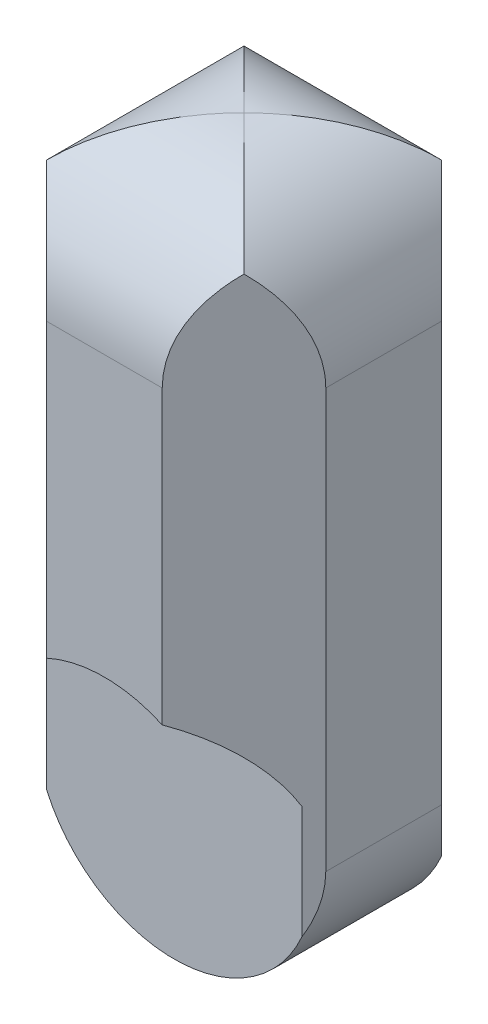
SolidWorks part; units mm, degrees
ref_plane "Front" through (0, 0, 0) normal (0, 0, 1) x (1, 0, 0)
ref_plane "Top" through (0, 0, 0) normal (0, 1, 0) x (1, 0, 0)
ref_plane "Right" through (0, 0, 0) normal (1, 0, 0) x (0, 0, -1)
sketch "草图2" plane through (0, 0, 0) normal (0, 1, 0) x (1, 0, 0)
  line L1 (8, 3.3137) -> (3.3137, 8)
  line L2 (3.3137, 8) -> (-3.3137, 8)
  line L3 (-3.3137, 8) -> (-8, 3.3137)
  line L4 (-8, 3.3137) -> (-8, -3.3137)
  line L5 (-8, -3.3137) -> (-3.3137, -8)
  line L6 (-3.3137, -8) -> (3.3137, -8)
  line L7 (3.3137, -8) -> (8, -3.3137)
  line L8 (8, -3.3137) -> (8, 3.3137)
  circle A0 centre (0, 0) radius 8 construction
extrude "凸台-拉伸1" add sketch "草图2" along normal blind 40
sketch "草图4" plane through (0, 0, 0) normal (0, 0, 1) x (1, 0, 0)
  line L2 (-8, 8) -> (-8, -3.6831)
  line L3 (-8, -3.6831) -> (8, -3.6831)
  line L4 (8, 8) -> (8, -3.6831)
  arc A0 (-8, 8) -> (8, 8) centre (0, 8) ccw
extrude "切除-拉伸1" cut sketch "草图4" against normal through all both and the other way through all
sketch "草图5" plane through (0, 0, 8) normal (0, 0, 1) x (1, 0, 0)
  circle A0 centre (0, 8) radius 8
extrude "切除-拉伸2" cut sketch "草图5" against normal blind 4
sketch "草图6" plane through (0, 0, -8) normal (0, 0, -1) x (-1, 0, 0)
  circle A0 centre (0, 8) radius 8
extrude "切除-拉伸3" cut sketch "草图6" against normal blind 4
sketch "草图7" plane through (0, 0, -8) normal (0, 0, -1) x (-1, 0, 0)
  line L2 (-8, 32) -> (-8, 48.9807)
  line L3 (-8, 48.9807) -> (8, 48.9807)
  line L4 (8, 32) -> (8, 48.9807)
  arc A0 (8, 32) -> (-8, 32) centre (0, 32) ccw
extrude "切除-拉伸4" cut sketch "草图7" against normal blind 100
sketch "草图8" plane through (-8, 0, 0) normal (-1, 0, 0) x (0, 0, 1)
  line L0 (0, 40) -> (0, 28.4584) construction
  line L1 (8, 40) -> (-8, 40) construction
  line L2 (3.3137, 32) -> (-3.3137, 32) construction
  line L5 (-8, 32) -> (-8, 42.1692)
  line L6 (-8, 42.1692) -> (8, 42.1692)
  line L7 (8, 32) -> (8, 42.1692)
  arc A0 (8, 32) -> (-8, 32) centre (0, 32) ccw
extrude "切除-拉伸5" cut sketch "草图8" against normal blind 100
